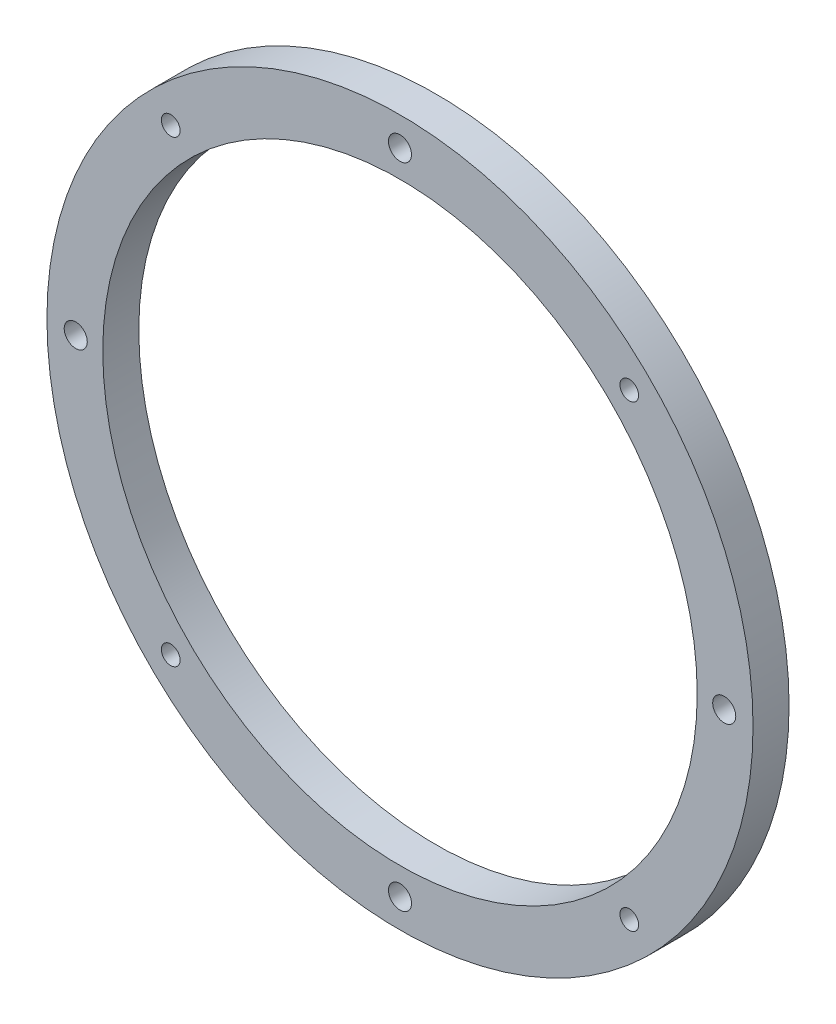
SolidWorks part; units mm, degrees
ref_plane "Front Plane" through (0, 0, 0) normal (0, 0, 1) x (1, 0, 0)
ref_plane "Top Plane" through (0, 0, 0) normal (0, 1, 0) x (1, 0, 0)
ref_plane "Right Plane" through (0, 0, 0) normal (1, 0, 0) x (0, 0, -1)
sketch "Sketch1" plane through (0, 0, 0) normal (0, 0, 1) x (1, 0, 0)
  line L0 (0, 0) -> (0, 1143) construction
  line L1 (0, 0) -> (808.2231, 808.2231) construction
  circle A0 centre (0, 0) radius 1047.783
  circle A1 centre (0, 0) radius 1244.6
  circle A2 centre (0, 1143) radius 40.64
  circle A3 centre (808.2231, 808.2231) radius 33.02
  circle A4 centre (1143, 0) radius 40.64
  circle A5 centre (808.2231, -808.2231) radius 33.02
  circle A6 centre (0, -1143) radius 40.64
  circle A7 centre (-808.2231, -808.2231) radius 33.02
  circle A8 centre (-1143, 0) radius 40.64
  circle A9 centre (-808.2231, 808.2231) radius 33.02
  circle A10 centre (0, 0) radius 1143 construction
  point P9 (0, 0)
  point P10 (0, 0)
  point P23 (0, 0)
  point P24 (0, 0)
  point P25 (0, 0)
  point P26 (0, 0)
  point P27 (-1143, 0)
  point P28 (0, 0)
  point P29 (-808.2231, -808.2231)
  point P30 (-808.2231, -808.2231)
  dimension "D1" = 2095.566
  dimension "D2" = 2489.2
  dimension "D3" = 81.28
  dimension "D7" = 66.04
  dimension "D4" = 1143
  dimension "D5" = 1143
  dimension "D6" = 45
  dimension "D8" = 4
extrude "Boss-Extrude2" add sketch "Sketch1" along normal blind 127
